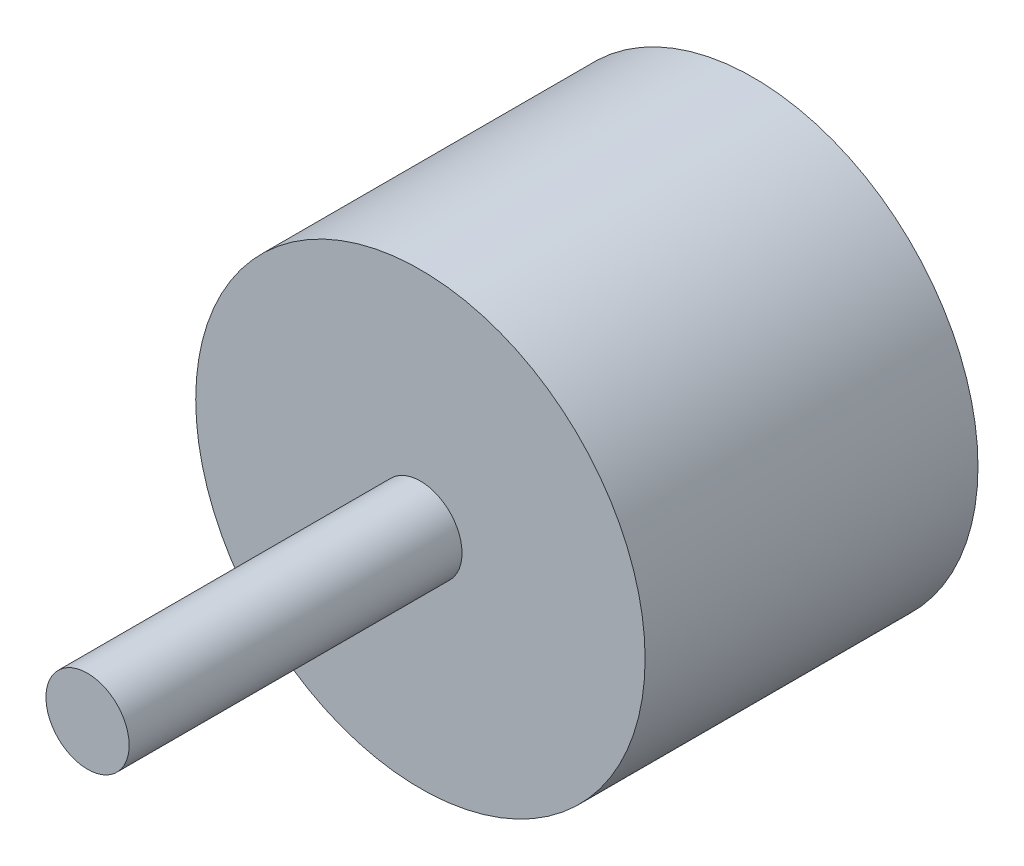
SolidWorks part; units mm, degrees
ref_plane "Front Plane" through (0, 0, 0) normal (0, 0, 1) x (1, 0, 0)
ref_plane "Top Plane" through (0, 0, 0) normal (0, 1, 0) x (1, 0, 0)
ref_plane "Right Plane" through (0, 0, 0) normal (1, 0, 0) x (0, 0, -1)
sketch "Sketch1" plane through (0, 0, 0) normal (0, 0, 1) x (1, 0, 0)
  circle A0 centre (0, 0) radius 27
extrude "Boss-Extrude1" add sketch "Sketch1" along normal blind 40
sketch "Sketch2" plane through (0, 0, 40) normal (0, 0, 1) x (1, 0, 0)
  circle A0 centre (0, 0) radius 5
extrude "Boss-Extrude2" add sketch "Sketch2" along normal blind 40
